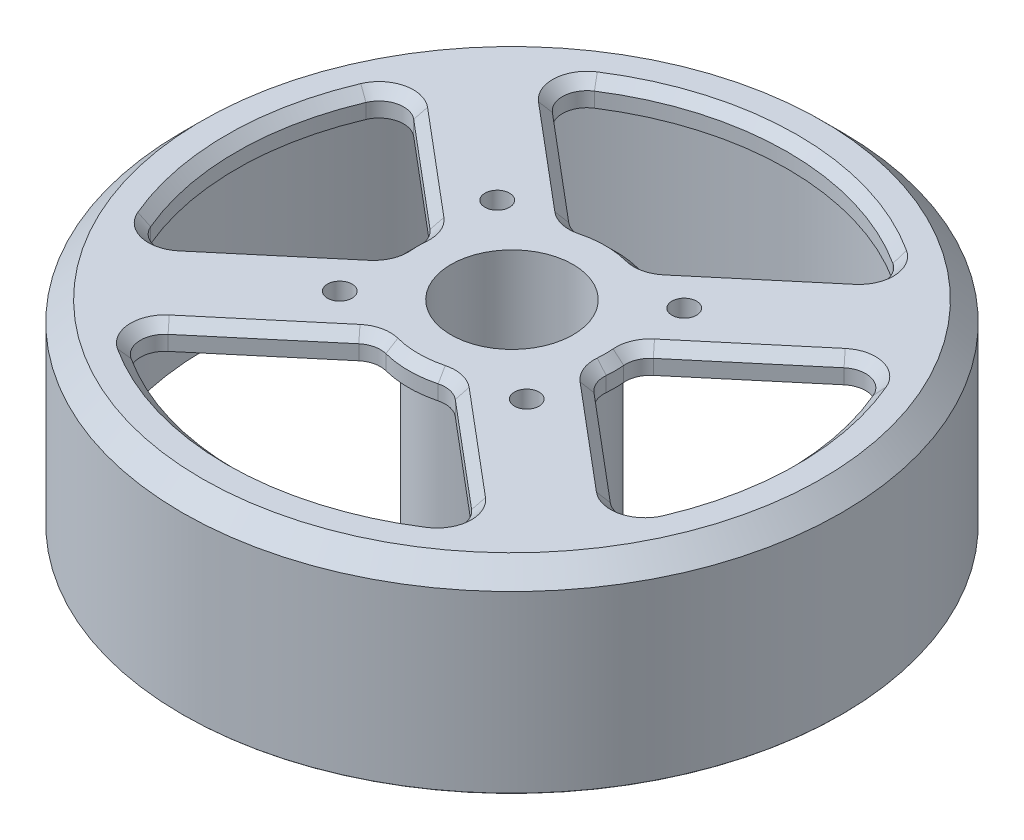
SolidWorks part; units mm, degrees
ref_plane "前视基准面" through (0, 0, 0) normal (0, 0, 1) x (1, 0, 0)
ref_plane "上视基准面" through (0, 0, 0) normal (0, 1, 0) x (1, 0, 0)
ref_plane "右视基准面" through (0, 0, 0) normal (1, 0, 0) x (0, 0, -1)
sketch "草图6" plane through (0, 0, 0) normal (0, 0, 1) x (1, 0, 0)
  line L0 (33.5, 0) -> (33.5, 19.8)
  line L1 (33.5, 19.8) -> (6.2, 19.8)
  line L2 (6.2, 19.8) -> (6.2, -5.6218)
  line L4 (6.2, -11.5) -> (6.2, -8.5)
  line L5 (6.2, -8.5) -> (9, -8.5)
  line L6 (9, -8.5) -> (9, -7.3)
  line L7 (9, -7.3) -> (8, -4)
  line L8 (8, -4) -> (8, 17.3)
  line L9 (8, 17.3) -> (31, 17.3)
  line L10 (31, 17.3) -> (31, 0)
  line L11 (31, 0) -> (33.5, 0)
  line L12 (0, 0) -> (0, 28.6903) construction
  line L13 (0, 0) -> (49.2309, 0) construction
  line L14 (6.2, -5.6218) -> (4.95, -5.6218)
  line L15 (4.95, -5.6218) -> (4.95, -11.5)
  line L17 (6.2, -11.5) -> (4.95, -11.5)
  dimension "D1" = 6.2
  dimension "D2" = 33.5
  dimension "D3" = 19.8
  dimension "D4" = 4.95
  dimension "D5" = 31.3
  dimension "D6" = 3
  dimension "D7" = 1.2
  dimension "D8" = 6.2
  dimension "D9" = 9
  dimension "D10" = 8
  dimension "D11" = 4
  dimension "D12" = 2.5
  dimension "D13" = 2.5
revolve "旋转1" add sketch "草图6" angle 360 about L12
sketch "草图7" plane through (0, 19.8, 0) normal (0, 1, 0) x (1, 0, 0)
  line L1 (9.5, 8) -> (-9.5, 8) construction
  line L2 (9.5, 8) -> (9.5, -8) construction
  line L3 (9.5, -8) -> (-9.5, -8) construction
  line L4 (-9.5, 8) -> (-9.5, -8) construction
  line L5 (9.5, 8) -> (-9.5, -8) construction
  line L6 (9.5, -8) -> (-9.5, 8) construction
  point P0 (0, 0)
  dimension "D1" = 16
  dimension "D2" = 19
hole_wizard "M3 螺纹孔1" positions "草图8" profile "草图9" tap size "M3" standard "GB" end condition through all
sketch "草图8" plane through (0, 19.8, 0) normal (0, 1, 0) x (1, 0, 0)
  point P0 (9.5, -8)
  point P3 (-9.5, -8)
  point P6 (-9.5, 8)
  point P9 (9.5, 8)
sketch "草图9" plane through (9.5, 19.8, 8) normal (1, 0, 0) x (0, 0, 1)
  line L0 (0, 0) -> (0, 31.3)
  line L1 (0, 31.3) -> (1.25, 31.3)
  line L2 (1.25, 31.3) -> (1.25, 0)
  line L5 (1.25, 0) -> (0, 0)
  line L11 (0, -6.35) -> (0, 107.95) construction
  dimension "通孔螺纹孔钻头直径" = 2.5
  dimension "通孔螺纹孔钻头深度" = 31.3
cosmetic thread "孔螺蚊线1" parameters "D2"=3
cosmetic thread "孔螺蚊线2" parameters "D2"=3
cosmetic thread "孔螺蚊线3" parameters "D2"=3
cosmetic thread "孔螺蚊线4" parameters "D2"=3
sketch "草图11" plane through (0, 19.8, 0) normal (0, 1, 0) x (1, 0, 0)
  line L0 (17.8526, 21.5705) -> (3.8418, 9.7719)
  line L7 (24.2939, -13.9214) -> (10.2832, -2.1228)
  line L8 (24.2939, 13.9214) -> (10.2832, 2.1228)
  line L9 (17.8526, -21.5705) -> (3.8418, -9.7719)
  line L13 (-3.8418, 9.7719) -> (-17.8526, 21.5705)
  line L16 (-10.2832, 2.1228) -> (-24.2939, 13.9214)
  line L17 (-3.8418, -9.7719) -> (-17.8526, -21.5705)
  line L18 (-10.2832, -2.1228) -> (-24.2939, -13.9214)
  arc A3 (3.8418, 9.7719) -> (-3.8418, 9.7719) centre (0, 0) ccw
  arc A4 (24.2939, -13.9214) -> (24.2939, 13.9214) centre (0, 0) ccw
  arc A5 (-17.8526, -21.5705) -> (17.8526, -21.5705) centre (0, 0) ccw
  arc A6 (-24.2939, 13.9214) -> (-24.2939, -13.9214) centre (0, 0) ccw
  arc A7 (17.8526, 21.5705) -> (-17.8526, 21.5705) centre (0, 0) ccw
  arc A8 (10.2832, -2.1228) -> (10.2832, 2.1228) centre (0, 0) ccw
  arc A9 (-3.8418, -9.7719) -> (3.8418, -9.7719) centre (0, 0) ccw
  arc A10 (-10.2832, 2.1228) -> (-10.2832, -2.1228) centre (0, 0) ccw
  point P0 (0, 0)
extrude "切除-拉伸1" cut sketch "草图11" against normal blind 10
chamfer "倒角1" distance 2 angle 45 1 edges at (0, 19.8, -33.5)
fillet "圆角1" radius 2.5 16 edges at (-17.8526, 18.55, 21.5705) (-3.8418, 18.55, 9.7719) (3.8418, 18.55, 9.7719) (17.8526, 18.55, 21.5705) (24.2939, 18.55, 13.9214) (10.2832, 18.55, 2.1228) (10.2832, 18.55, -2.1228) (24.2939, 18.55, -13.9214) (17.8526, 18.55, -21.5705) (-17.8526, 18.55, -21.5705) (-3.8418, 18.55, -9.7719) (3.8418, 18.55, -9.7719) (-24.2939, 18.55, 13.9214) (-10.2832, 18.55, 2.1228) (-10.2832, 18.55, -2.1228) (-24.2939, 18.55, -13.9214)
chamfer "倒角2" distance 1 angle 45 32 edges at (10.1616, 19.8, 15.0939) (3.8415, 19.8, 10.1378) (16.3064, 19.8, 21.5951) (0, 19.8, 10.5) (0, 19.8, 28) (-3.8415, 19.8, 10.1378) (-16.3064, 19.8, 21.5951) (-10.1616, 19.8, 15.0939) (16.603, 19.8, 7.4448) (24.0551, 19.8, 12.3935) (10.6437, 19.8, 2.0602) (28, 19.8, 0) (10.5, 19.8, 0) (24.0551, 19.8, -12.3935) (10.6437, 19.8, -2.0602) (16.603, 19.8, -7.4448) (0, 19.8, -10.5) (3.8415, 19.8, -10.1378) (-3.8415, 19.8, -10.1378) (10.1616, 19.8, -15.0939) (-10.1616, 19.8, -15.0939) (16.3064, 19.8, -21.5951) (-16.3064, 19.8, -21.5951) (0, 19.8, -28) (-10.5, 19.8, 0) (-10.6437, 19.8, -2.0602) (-10.6437, 19.8, 2.0602) (-16.603, 19.8, -7.4448) (-16.603, 19.8, 7.4448) (-24.0551, 19.8, -12.3935) (-24.0551, 19.8, 12.3935) (-28, 19.8, 0)
chamfer "倒角3" distance 0.05 angle 45 1 edges at (0, 0, -33.5)
chamfer "倒角4" distance 0.05 angle 45 1 edges at (0, -11.5, -6.2)
